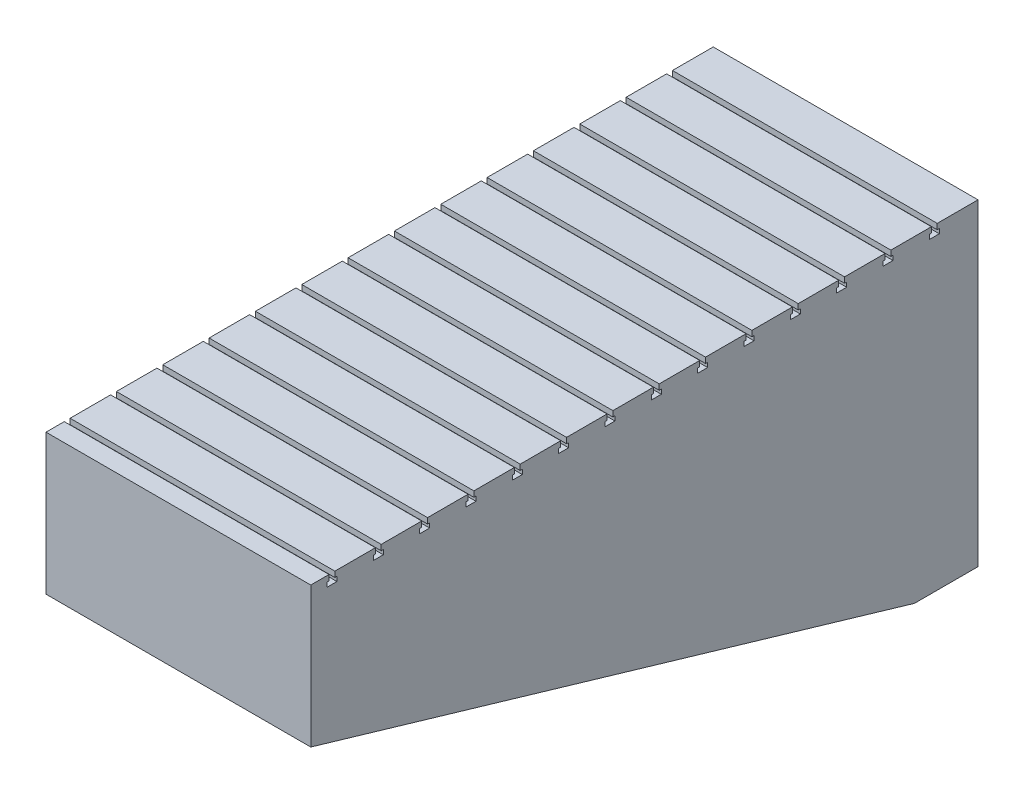
SolidWorks part; units mm, degrees
ref_plane "Front Plane" through (0, 0, 0) normal (0, 0, 1) x (1, 0, 0)
ref_plane "Top Plane" through (0, 0, 0) normal (0, 1, 0) x (1, 0, 0)
ref_plane "Right Plane" through (0, 0, 0) normal (1, 0, 0) x (0, 0, -1)
sketch "Sketch4" plane through (0, 0, 0) normal (1, 0, 0) x (0, 0, -1)
  line L0 (0, 0) -> (-2520, 0)
  line L1 (-2520, 0) -> (-2520, -530)
  line L2 (-2520, -530) -> (-240, -1200)
  line L3 (-240, -1200) -> (0, -1200)
  line L4 (0, -1200) -> (0, 0)
  dimension "D1" = 2520
  dimension "D2" = 1200
  dimension "D3" = 530
  dimension "D4" = 240
extrude "Boss-Extrude1" add sketch "Sketch4" along normal blind 1000
sketch "Sketch6" plane through (0, 0, 0) normal (1, 0, 0) x (0, 0, -1)
  line L0 (0, 0) -> (-2520, 0) construction
  line L1 (-154, 0) -> (-176, 0)
  line L2 (-154, 0) -> (-154, -21)
  line L3 (-154, -21) -> (-146.1, -21)
  line L4 (-146.1, -21) -> (-146.1, -38)
  line L5 (-146.1, -38) -> (-183.9, -38)
  line L6 (-183.9, -38) -> (-183.9, -21)
  line L7 (-183.9, -21) -> (-176, -21)
  line L8 (-176, -21) -> (-176, 0)
  line L9 (-165, -141.8364) -> (-165, 56.6562) construction
  line L11 (0, -1200) -> (0, 0) construction
  dimension "D1" = 22
  dimension "D2" = 37.8
  dimension "D3" = 21
  dimension "D4" = 38
  dimension "D5" = 165
  dimension "D6" = 154
extrude "Cut-Extrude1" cut sketch "Sketch6" along normal up to next
pattern_linear "LPattern1" count 14 spacing 175 along (0, 0, 1) of "Cut-Extrude1"
